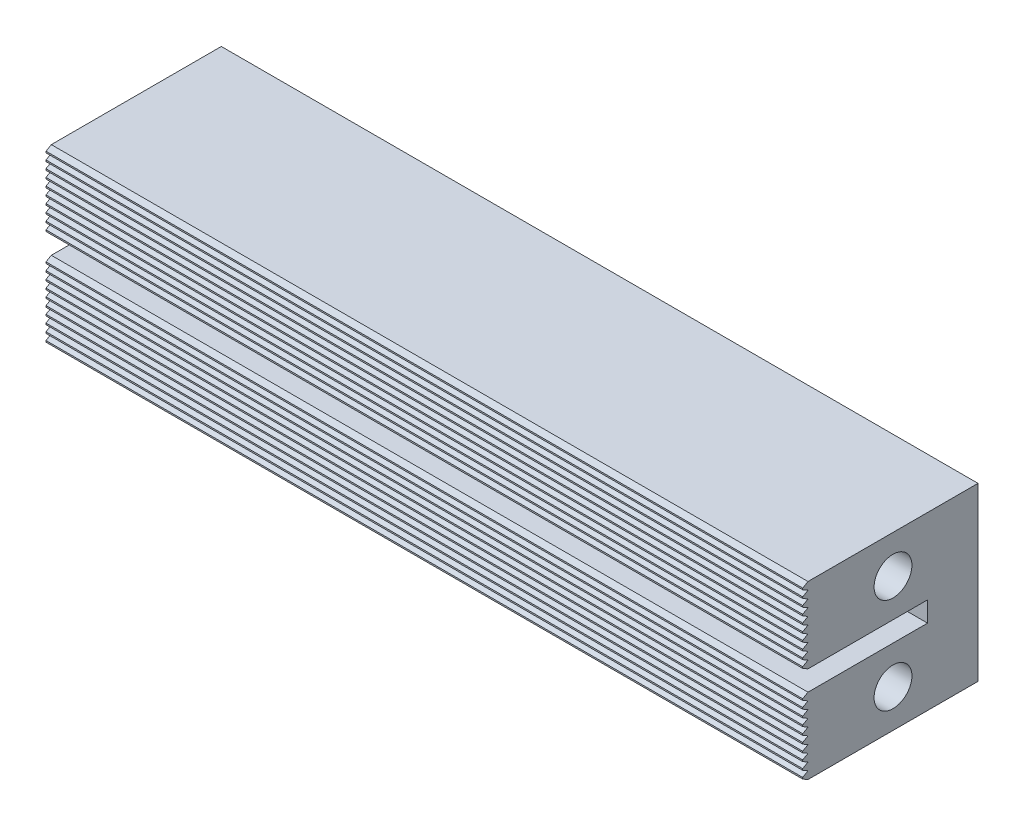
SolidWorks part; units mm, degrees
ref_plane "Front Plane" through (0, 0, 0) normal (0, 0, 1) x (1, 0, 0)
ref_plane "Top Plane" through (0, 0, 0) normal (0, 1, 0) x (1, 0, 0)
ref_plane "Right Plane" through (0, 0, 0) normal (1, 0, 0) x (0, 0, -1)
sketch "Sketch1" plane through (0, 0, 0) normal (0, 0, 1) x (1, 0, 0)
  line L5 (0, 0) -> (150, 0)
  line L6 (0, 0) -> (0, 34)
  line L7 (0, 34) -> (150, 34)
  line L8 (150, 0) -> (150, 34)
  dimension "D1" = 34
  dimension "D2" = 150
extrude "Boss-Extrude1" add sketch "Sketch1" along normal blind 35
sketch "Sketch2" plane through (150, 0, 0) normal (1, 0, 0) x (0, 0, -1)
  line L0 (-35, 17) -> (-35, 19)
  line L1 (-35, 0) -> (-35, 34) construction
  line L2 (-35, 19) -> (-10, 19)
  line L3 (-10, 19) -> (-10, 15)
  line L4 (-10, 15) -> (-35, 15)
  line L5 (-35, 15) -> (-35, 17)
  line L6 (-35, 0) -> (0, 0) construction
  dimension "D1" = 25
  dimension "D2" = 15
  dimension "D3" = 4
extrude "Cut-Extrude1" cut sketch "Sketch2" against normal blind 160
sketch "Sketch3" plane through (150, 0, 0) normal (1, 0, 0) x (0, 0, -1)
  line L1 (-35, 31.75) -> (-33.7, 31)
  line L3 (-33.7, 31) -> (-35, 30.25)
  line L6 (-35, 34) -> (0, 34) construction
  line L8 (-35, 19) -> (-35, 34) construction
  line L9 (-35, 33.25) -> (-33.7, 34)
  line L10 (-35, 33.25) -> (-31.5992, 33.25) construction
  line L11 (-35, 33.25) -> (-33.7, 32.5)
  line L12 (-35, 33.25) -> (-35, 31.75)
  line L13 (-33.7, 32.5) -> (-35, 31.75)
  line L14 (-33.7, 34) -> (-35, 34)
  line L15 (-35, 34) -> (-35, 33.25)
  line L16 (-35, 31.75) -> (-35, 30.25)
  line L17 (-35, 30.25) -> (-33.7, 29.5)
  line L18 (-33.7, 29.5) -> (-35, 28.75)
  line L19 (-35, 30.25) -> (-35, 28.75)
  line L20 (-35, 28.75) -> (-33.7, 28)
  line L21 (-33.7, 28) -> (-35, 27.25)
  line L22 (-35, 28.75) -> (-35, 27.25)
  line L23 (-35, 27.25) -> (-33.7, 26.5)
  line L24 (-33.7, 26.5) -> (-35, 25.75)
  line L25 (-35, 27.25) -> (-35, 25.75)
  line L26 (-35, 25.75) -> (-33.7, 25)
  line L27 (-33.7, 25) -> (-35, 24.25)
  line L28 (-35, 25.75) -> (-35, 24.25)
  line L29 (-35, 24.25) -> (-33.7, 23.5)
  line L30 (-33.7, 23.5) -> (-35, 22.75)
  line L31 (-35, 24.25) -> (-35, 22.75)
  line L32 (-35, 22.75) -> (-33.7, 22)
  line L33 (-33.7, 22) -> (-35, 21.25)
  line L34 (-35, 22.75) -> (-35, 21.25)
  line L35 (-35, 21.25) -> (-33.7, 20.5)
  line L36 (-33.7, 20.5) -> (-35, 19.75)
  line L37 (-35, 21.25) -> (-35, 19.75)
  line L38 (-35, 19.75) -> (-33.7, 19)
  line L39 (-33.7, 19) -> (-35, 18.25)
  line L40 (-35, 19.75) -> (-35, 18.25)
  dimension "D1" = 119.982
  dimension "D2" = 1.5
  dimension "D3" = 1.3
  dimension "D4" = 0.75
  dimension "D6" = 1.5
  dimension "D5" = 10
extrude "Cut-Extrude7" cut sketch "Sketch3" against normal blind 160 contours L13 L11 L28 | L28 L9 L21 | L3 L1 L28 | L18 L17 L28 | L21 L20 L28 | L24 L23 L28 | L27 L26 L28 | L30 L29 L28 | L33 L32 L28 | L36 L35 L28 | L38 L28 L27
ref_plane "Plane2" through (0, 17, 0) normal (0, 1, 0) x (1, 0, 0)
mirror "Mirror1" about plane through (0, 17, 0) normal (0, 1, 0) of "Cut-Extrude7"
sketch "Sketch6" plane through (150, 0, 0) normal (1, 0, 0) x (0, 0, -1)
  line L1 (-35, 34) -> (-34.75, 34)
  line L2 (-35, 34) -> (-35, 0)
  line L3 (-35, 0) -> (-34.75, 0)
  line L4 (-34.75, 34) -> (-34.75, 0)
  line L5 (0, 0) -> (0, 34) construction
  line L6 (-33.7, 0) -> (0, 0) construction
  dimension "D1" = 0.25
  dimension "D2" = 34
  dimension "D3" = 1.3
extrude "Cut-Extrude8" cut sketch "Sketch6" against normal blind 160
sketch "Sketch7" plane through (150, 0, 0) normal (1, 0, 0) x (0, 0, -1)
  line L0 (-16.85, 34) -> (-16.85, 26.5) construction
  line L2 (-33.7, 34) -> (0, 34) construction
  line L3 (18.535, 17) -> (-18.535, 17) construction
  circle A0 centre (-16.85, 26.5) radius 3.75
  circle A1 centre (-16.85, 7.5) radius 3.75
  dimension "D1" = 7.5
  dimension "D2" = 7.5
extrude "Cut-Extrude9" cut sketch "Sketch7" against normal blind 160
sketch "Sketch8" plane through (0, 0, 10) normal (0, 0, 1) x (1, 0, 0)
  line L0 (150, 34) -> (100, 34) construction
  line L1 (0, 34) -> (150, 34) construction
  line L2 (100, 41.7873) -> (100, -6.1853) construction
  line L3 (49.3002, 17) -> (168.0873, 17) construction
  line L5 (18.535, 17) -> (-18.535, 17) construction
  line L6 (150, 15) -> (150, 19) construction
  line L7 (75, 41.7873) -> (75, -6.1853) construction
  circle A0 centre (100, 17) radius 3.5
  circle A1 centre (50, 17) radius 3.5
  point P8 (50, 17.801)
  dimension "D1" = 2
  dimension "D2" = 7
  dimension "D3" = 50
  dimension "D4" = 50
  dimension "D5" = 2
extrude "Cut-Extrude10" cut sketch "Sketch8" against normal blind 5 from offset 5
